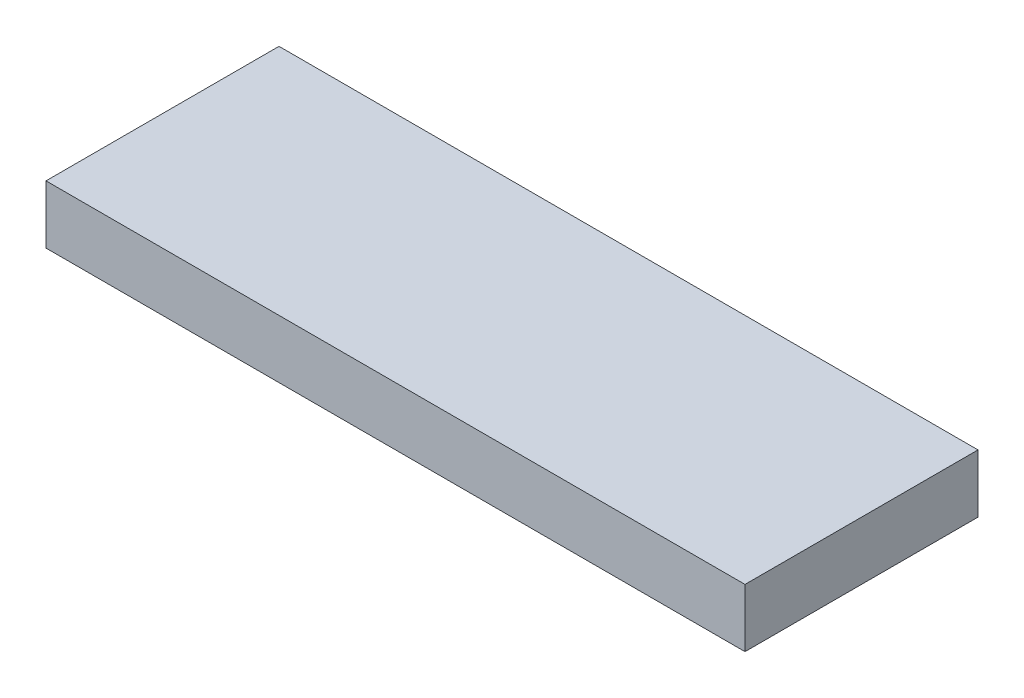
SolidWorks part; units mm, degrees
ref_plane "Front Plane" through (0, 0, 0) normal (0, 0, 1) x (1, 0, 0)
ref_plane "Top Plane" through (0, 0, 0) normal (0, 1, 0) x (1, 0, 0)
ref_plane "Right Plane" through (0, 0, 0) normal (1, 0, 0) x (0, 0, -1)
sketch "Sketch2" plane through (0, 0, 0) normal (0, 1, 0) x (1, 0, 0)
  line L1 (-57.0255, 12.5755) -> (19.1745, 12.5755)
  line L2 (-57.0255, 12.5755) -> (-57.0255, -12.8245)
  line L3 (-57.0255, -12.8245) -> (19.1745, -12.8245)
  line L4 (19.1745, 12.5755) -> (19.1745, -12.8245)
  dimension "D1" = 25.4
  dimension "D2" = 76.2
extrude "Boss-Extrude1" add sketch "Sketch2" along normal blind 6.35
